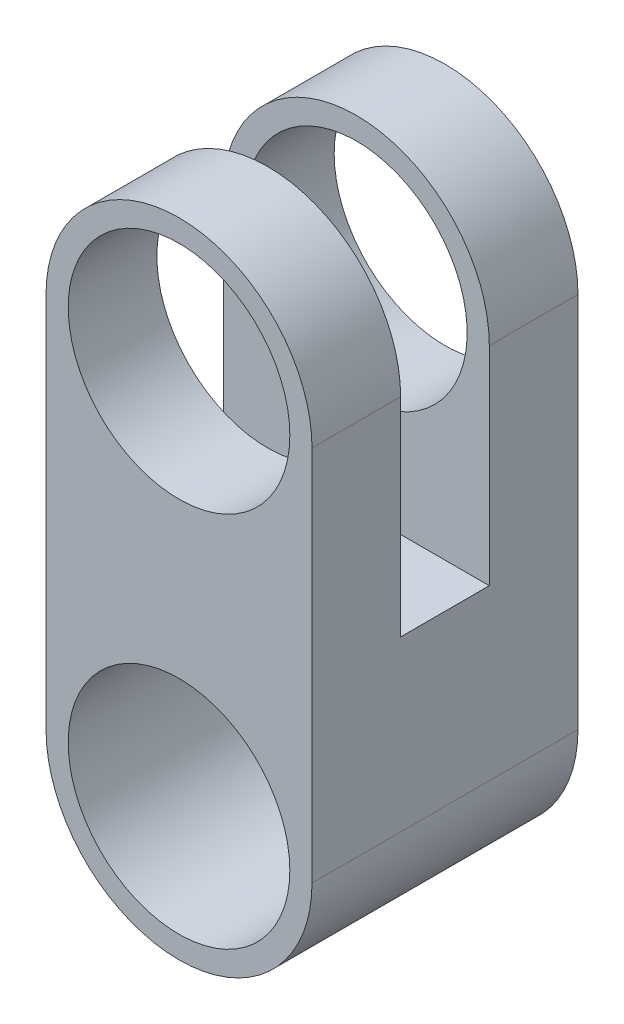
SolidWorks part; units mm, degrees
ref_plane "Front Plane" through (0, 0, 0) normal (0, 0, 1) x (1, 0, 0)
ref_plane "Top Plane" through (0, 0, 0) normal (0, 1, 0) x (1, 0, 0)
ref_plane "Right Plane" through (0, 0, 0) normal (1, 0, 0) x (0, 0, -1)
sketch "Sketch1" plane through (0, 0, 0) normal (0, 0, 1) x (1, 0, 0)
  line L0 (0, 37.0662) -> (0, 28.5662) construction
  line L2 (3, 37.0662) -> (3, 28.5662)
  line L3 (-3, 37.0662) -> (-3, 28.5662)
  arc A0 (3, 37.0662) -> (-3, 37.0662) centre (0, 37.0662) ccw
  arc A1 (-3, 28.5662) -> (3, 28.5662) centre (0, 28.5662) ccw
  circle A2 centre (0, 37.0662) radius 2.5
  circle A3 centre (0, 28.5662) radius 2.5
  point P5 (0, 32.8162)
extrude "Boss-Extrude1" add sketch "Sketch1" along normal blind 6
sketch "Sketch2" plane through (-3, 0, 0) normal (-1, 0, 0) x (0, 0, 1)
  line L1 (6, 37.0662) -> (0, 37.0662) construction
  line L3 (2, 37.0662) -> (2, 41.7924)
  line L4 (2, 41.7924) -> (4, 41.7924)
  line L5 (4, 41.7924) -> (4, 37.0662)
  line L6 (2, 37.0662) -> (2, 32.3763)
  line L7 (2, 32.3763) -> (4, 32.3763)
  line L8 (4, 32.3763) -> (4, 37.0662)
extrude "Cut-Extrude2" cut sketch "Sketch2" against normal through all
